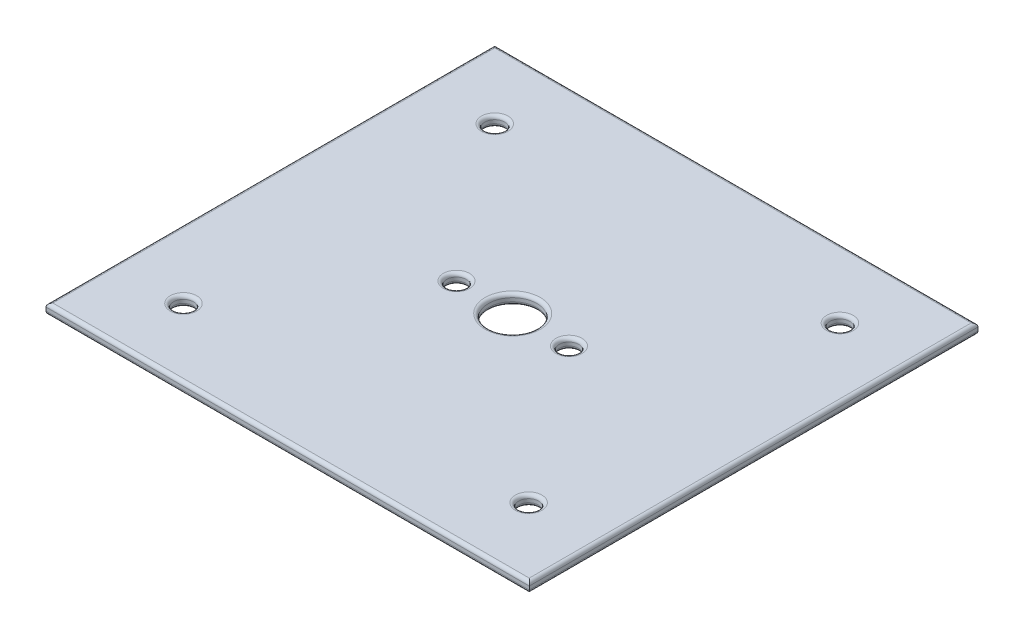
SolidWorks part; units mm, degrees
ref_plane "Front Plane" through (0, 0, 0) normal (0, 0, 1) x (1, 0, 0)
ref_plane "Top Plane" through (0, 0, 0) normal (0, 1, 0) x (1, 0, 0)
ref_plane "Right Plane" through (0, 0, 0) normal (1, 0, 0) x (0, 0, -1)
sketch "Sketch1" plane through (0, 0, 0) normal (0, 1, 0) x (1, 0, 0)
  line L1 (0, 0) -> (70, 0)
  line L2 (0, 0) -> (0, 65)
  line L3 (0, 65) -> (70, 65)
  line L4 (70, 0) -> (70, 65)
  dimension "D1" = 70
  dimension "D2" = 65
extrude "Boss-Extrude1" add sketch "Sketch1" along normal blind 1.5
sketch "Sketch3" plane through (0, 1.5, 0) normal (0, 1, 0) x (1, 0, 0)
  line L0 (-966.0978, 32.5) -> (49033.9022, 32.5) construction
  line L1 (70, 65) -> (0, 65) construction
  line L2 (0, 0) -> (70, 0) construction
  line L3 (-947.7109, 55) -> (49052.2891, 55) construction
  line L4 (-950.2815, 8.43) -> (-950.2815, 50008.43) construction
  line L5 (60, -969.9215) -> (60, 49030.0785) construction
  line L6 (10, -967.5) -> (10, 49032.5) construction
  line L7 (-956.6902, 10) -> (49043.3098, 10) construction
  line L8 (70, 0) -> (70, 65) construction
  line L9 (0, 65) -> (0, 0) construction
  line L10 (0, 39.25) -> (24.5819, 39.25) construction
  line L11 (0, 25.75) -> (24.5843, 25.75) construction
  line L12 (0, 39.25) -> (0, 25.75) construction
  line L13 (47.6017, -967.496) -> (47.6017, 49032.504) construction
  line L14 (22.6037, -967.5003) -> (22.6037, 49032.4997) construction
  circle A0 centre (60, 55) radius 1.4224
  circle A1 centre (60, 9.9121) radius 1.4224
  circle A2 centre (10, 9.9121) radius 1.4224
  circle A3 centre (10, 55) radius 1.4224
  arc A4 (24.5843, 25.75) -> (24.5819, 39.25) centre (35.1027, 32.5019) ccw construction
  circle A5 centre (35.1027, 32.5019) radius 3.5
  circle A6 centre (43.2517, 32.5) radius 1.4
  arc A7 (24.5843, 25.75) -> (24.5819, 39.25) centre (35.1027, 32.5019) cw construction
  circle A8 centre (26.9537, 32.5) radius 1.4
  point P39 (47.6017, 32.504)
  point P43 (22.6037, 32.4997)
  dimension "D7" = 2.8448
  dimension "D8" = 2.8448
  dimension "D9" = 2.8448
  dimension "D10" = 2.8448
  dimension "D14" = 12.499
  dimension "D15" = 7
  dimension "D16" = 4.35
  dimension "D17" = 2.8
  dimension "D18" = 2.8
  dimension "D19" = 4.35
  dimension "D1" = 32.5
  dimension "D2" = 32.5
  dimension "D3" = 10
  dimension "D4" = 10
  dimension "D5" = 10
  dimension "D6" = 10
  dimension "D11" = 0
  dimension "D12" = 6.75
  dimension "D13" = 6.75
extrude "Cut-Extrude1" cut sketch "Sketch3" against normal blind 10
fillet "Fillet1" radius 0.5 22 edges at (35, 0, 0) (70, 0, -32.5) (35, 0, -65) (0, 0, -32.5) (60, 0, -56.4224) (26.9537, 0, -33.9) (43.2517, 0, -33.9) (35.1027, 0, -36.0019) (10, 0, -56.4224) (10, 0, -11.3345) (60, 0, -11.3345) (35, 1.5, -65) (70, 1.5, -32.5) (35, 1.5, 0) (0, 1.5, -32.5) (60, 1.5, -53.5776) (26.9537, 1.5, -31.1) (43.2517, 1.5, -31.1) (35.1027, 1.5, -29.0019) (10, 1.5, -53.5776) (10, 1.5, -8.4897) (60, 1.5, -8.4897)
